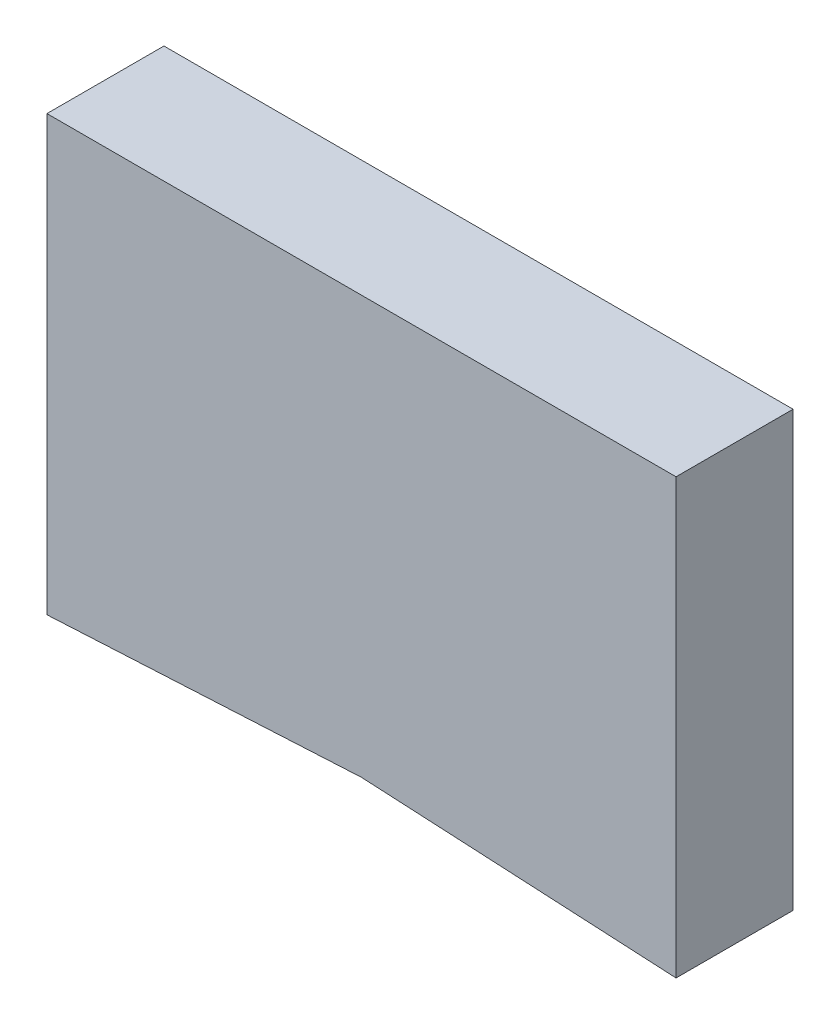
SolidWorks part; units mm, degrees
material "K110"
ref_plane "Front Plane" through (0, 0, 0) normal (0, 0, 1) x (1, 0, 0)
ref_plane "Top Plane" through (0, 0, 0) normal (0, 1, 0) x (1, 0, 0)
ref_plane "Right Plane" through (0, 0, 0) normal (1, 0, 0) x (0, 0, -1)
sketch "Sketch1" plane through (0, 0, 0) normal (0, 1, 0) x (1, 0, 0)
  line L1 (-40, -7.44) -> (40, -7.44)
  line L2 (-40, -7.44) -> (-40, 7.44)
  line L3 (-40, 7.44) -> (40, 7.44)
  line L4 (40, -7.44) -> (40, 7.44)
  line L5 (-40, -7.44) -> (40, 7.44) construction
  line L6 (-40, 7.44) -> (40, -7.44) construction
  point P0 (0, 0)
  dimension "D1" = 80
  dimension "D2" = 14.88
extrude "Boss-Extrude1" add sketch "Sketch1" against normal blind 55.2
sketch "Sketch3" plane through (0, 0, -7.44) normal (0, 0, -1) x (-1, 0, 0)
  line L0 (40, -55.2) -> (0, -53.1037)
  line L1 (0, -53.1037) -> (-40, -55.2)
  line L2 (-40, -55.2) -> (40, -55.2)
  point P4 (0, 0)
  point P7 (0, 0)
  point P9 (0, 0)
  dimension "D1" = 3
  dimension "D2" = 2.0963
extrude "Cut-Extrude1" cut sketch "Sketch3" against normal through all
